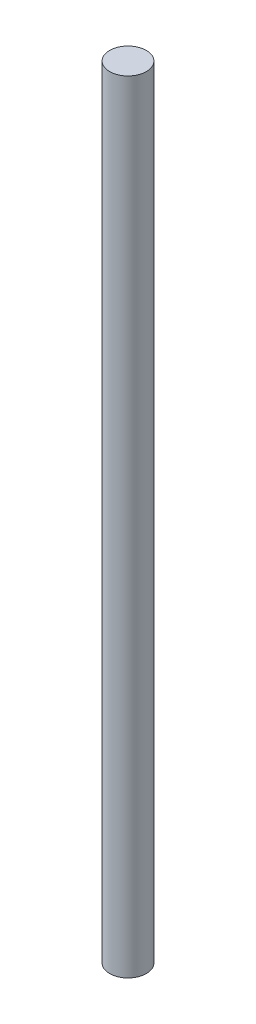
SolidWorks part; units mm, degrees
ref_plane "Front Plane" through (0, 0, 0) normal (0, 0, 1) x (1, 0, 0)
ref_plane "Top Plane" through (0, 0, 0) normal (0, 1, 0) x (1, 0, 0)
ref_plane "Right Plane" through (0, 0, 0) normal (1, 0, 0) x (0, 0, -1)
sketch "Sketch1" plane through (0, 0, 0) normal (0, 1, 0) x (1, 0, 0)
  circle A0 centre (0, 0) radius 6.2
  dimension "D1" = 12.4
extrude "Boss-Extrude1" add sketch "Sketch1" along normal blind 264
